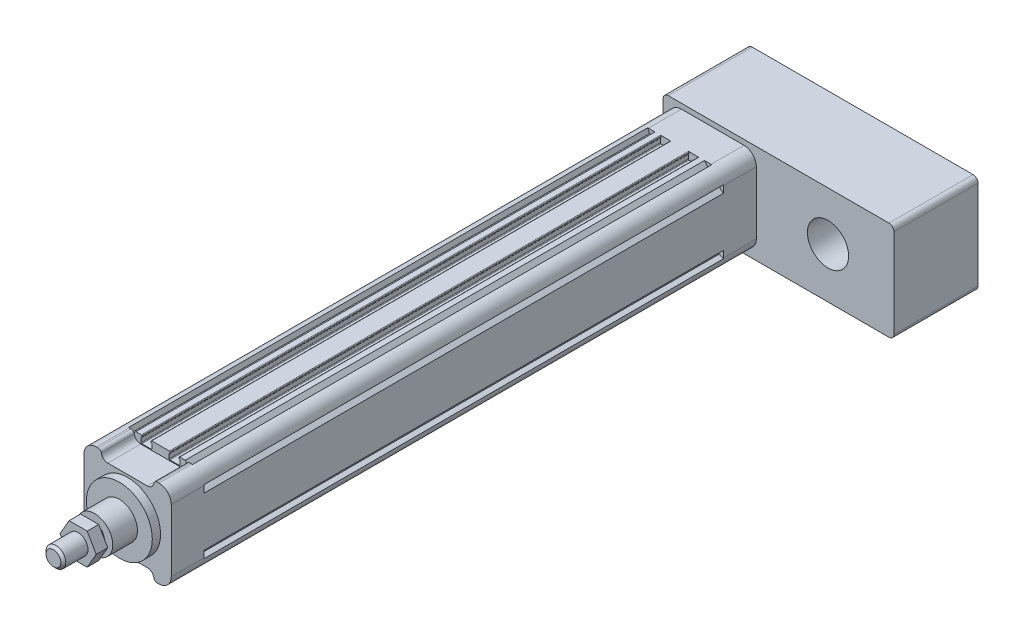
SolidWorks part; units mm, degrees
ref_plane "Front" through (0, 0, 0) normal (0, 0, 1) x (1, 0, 0)
ref_plane "Top" through (0, 0, 0) normal (0, 1, 0) x (1, 0, 0)
ref_plane "Right" through (0, 0, 0) normal (1, 0, 0) x (0, 0, -1)
sketch "草图1" plane through (0, 0, 0) normal (0, 0, 1) x (1, 0, 0)
  line L0 (19.7737, 3) -> (23.3, 3)
  line L1 (23.3, 3) -> (23.3, -3)
  line L2 (23.3, -3) -> (19.7737, -3)
  line L3 (-19.7737, -3) -> (-23.3, -3)
  line L4 (-23.3, -3) -> (-23.3, 3)
  line L5 (-23.3, 3) -> (-19.7737, 3)
  line L6 (-18.2, 24) -> (-19.4434, 26.4869)
  line L7 (-26.4869, 19.4434) -> (-24, 18.2)
  line L8 (-24, 18.2) -> (-24, 17.1)
  line L9 (-24, 17.1) -> (-26.5, 15)
  line L10 (-26.5, 15) -> (-26.5, -15)
  line L11 (-26.5, -15) -> (-24, -17.1)
  line L12 (-24, -17.1) -> (-24, -18.2)
  line L13 (-24, -18.2) -> (-26.4869, -19.4434)
  line L14 (-19.4434, -26.4869) -> (-18.2, -24)
  line L15 (-18.2, -24) -> (-17.1, -24)
  line L16 (-17.1, -24) -> (-15, -26.5)
  line L17 (-15, -26.5) -> (-11.65, -26.5)
  line L18 (-11.25, -26.1) -> (-11.25, -25.6)
  line L19 (-11.65, -25.2) -> (-11.75, -25.2)
  line L20 (-11.75, -25.2) -> (-11.75, -22.4)
  line L21 (-11.35, -22) -> (-5.65, -22)
  line L22 (-5.25, -22.4) -> (-5.25, -25.2)
  line L23 (-5.25, -25.2) -> (-5.35, -25.2)
  line L24 (-5.75, -25.6) -> (-5.75, -26.1)
  line L25 (-5.35, -26.5) -> (5.35, -26.5)
  line L26 (5.75, -26.1) -> (5.75, -25.6)
  line L27 (5.35, -25.2) -> (5.25, -25.2)
  line L28 (5.25, -25.2) -> (5.25, -22.4)
  line L29 (5.65, -22) -> (11.35, -22)
  line L30 (11.75, -22.4) -> (11.75, -25.2)
  line L31 (11.75, -25.2) -> (11.65, -25.2)
  line L32 (11.25, -25.6) -> (11.25, -26.1)
  line L33 (11.65, -26.5) -> (15, -26.5)
  line L34 (15, -26.5) -> (17.1, -24)
  line L35 (17.1, -24) -> (18.2, -24)
  line L36 (18.2, -24) -> (19.4434, -26.4869)
  line L37 (26.4869, -19.4434) -> (24, -18.2)
  line L38 (24, -18.2) -> (24, -17.1)
  line L39 (24, -17.1) -> (26.5, -15)
  line L40 (26.5, -15) -> (26.5, 15)
  line L41 (26.5, 15) -> (24, 17.1)
  line L42 (24, 17.1) -> (24, 18.2)
  line L43 (24, 18.2) -> (26.4869, 19.4434)
  line L44 (19.4434, 26.4869) -> (18.2, 24)
  line L45 (18.2, 24) -> (17.1, 24)
  line L46 (17.1, 24) -> (15, 26.5)
  line L47 (15, 26.5) -> (11.65, 26.5)
  line L48 (11.25, 26.1) -> (11.25, 25.6)
  line L49 (11.65, 25.2) -> (11.75, 25.2)
  line L50 (11.75, 25.2) -> (11.75, 22.4)
  line L51 (11.35, 22) -> (5.65, 22)
  line L52 (5.25, 22.4) -> (5.25, 25.2)
  line L53 (5.25, 25.2) -> (5.35, 25.2)
  line L54 (5.75, 25.6) -> (5.75, 26.1)
  line L55 (5.35, 26.5) -> (-5.35, 26.5)
  line L56 (-5.75, 26.1) -> (-5.75, 25.6)
  line L57 (-5.35, 25.2) -> (-5.25, 25.2)
  line L58 (-5.25, 25.2) -> (-5.25, 22.4)
  line L59 (-5.65, 22) -> (-11.35, 22)
  line L60 (-11.75, 22.4) -> (-11.75, 25.2)
  line L61 (-11.75, 25.2) -> (-11.65, 25.2)
  line L62 (-11.25, 25.6) -> (-11.25, 26.1)
  line L63 (-11.65, 26.5) -> (-15, 26.5)
  line L64 (-15, 26.5) -> (-17.1, 24)
  line L65 (-17.1, 24) -> (-18.2, 24)
  arc A0 (19.7737, 3) -> (-19.7737, 3) centre (0, 0) ccw
  arc A1 (-19.7737, -3) -> (19.7737, -3) centre (0, 0) ccw
  circle A2 centre (19, 19) radius 2.1
  circle A3 centre (19, -19) radius 2.1
  circle A4 centre (-19, -19) radius 2.1
  circle A5 centre (-19, 19) radius 2.1
  arc A6 (-19.4434, 26.4869) -> (-26.4869, 19.4434) centre (-19, 19) ccw
  arc A7 (-26.4869, -19.4434) -> (-19.4434, -26.4869) centre (-19, -19) ccw
  arc A8 (-11.65, -26.5) -> (-11.25, -26.1) centre (-11.65, -26.1) ccw
  arc A9 (-11.25, -25.6) -> (-11.65, -25.2) centre (-11.65, -25.6) ccw
  arc A10 (-11.35, -22) -> (-11.75, -22.4) centre (-11.35, -22.4) ccw
  arc A11 (-5.25, -22.4) -> (-5.65, -22) centre (-5.65, -22.4) ccw
  arc A12 (-5.35, -25.2) -> (-5.75, -25.6) centre (-5.35, -25.6) ccw
  arc A13 (-5.75, -26.1) -> (-5.35, -26.5) centre (-5.35, -26.1) ccw
  arc A14 (5.35, -26.5) -> (5.75, -26.1) centre (5.35, -26.1) ccw
  arc A15 (5.75, -25.6) -> (5.35, -25.2) centre (5.35, -25.6) ccw
  arc A16 (5.65, -22) -> (5.25, -22.4) centre (5.65, -22.4) ccw
  arc A17 (11.75, -22.4) -> (11.35, -22) centre (11.35, -22.4) ccw
  arc A18 (11.65, -25.2) -> (11.25, -25.6) centre (11.65, -25.6) ccw
  arc A19 (11.25, -26.1) -> (11.65, -26.5) centre (11.65, -26.1) ccw
  arc A20 (19.4434, -26.4869) -> (26.4869, -19.4434) centre (19, -19) ccw
  arc A21 (26.4869, 19.4434) -> (19.4434, 26.4869) centre (19, 19) ccw
  arc A22 (11.65, 26.5) -> (11.25, 26.1) centre (11.65, 26.1) ccw
  arc A23 (11.25, 25.6) -> (11.65, 25.2) centre (11.65, 25.6) ccw
  arc A24 (11.35, 22) -> (11.75, 22.4) centre (11.35, 22.4) ccw
  arc A25 (5.25, 22.4) -> (5.65, 22) centre (5.65, 22.4) ccw
  arc A26 (5.35, 25.2) -> (5.75, 25.6) centre (5.35, 25.6) ccw
  arc A27 (5.75, 26.1) -> (5.35, 26.5) centre (5.35, 26.1) ccw
  arc A28 (-5.35, 26.5) -> (-5.75, 26.1) centre (-5.35, 26.1) ccw
  arc A29 (-5.75, 25.6) -> (-5.35, 25.2) centre (-5.35, 25.6) ccw
  arc A30 (-5.65, 22) -> (-5.25, 22.4) centre (-5.65, 22.4) ccw
  arc A31 (-11.75, 22.4) -> (-11.35, 22) centre (-11.35, 22.4) ccw
  arc A32 (-11.65, 25.2) -> (-11.25, 25.6) centre (-11.65, 25.6) ccw
  arc A33 (-11.25, 26.1) -> (-11.65, 26.5) centre (-11.65, 26.1) ccw
extrude "凸台-拉伸1" add sketch "草图1" along normal blind 315
sketch "草图6" plane through (0, 0, 315) normal (0, 0, 1) x (1, 0, 0)
  line L0 (0, 0) -> (19, 0) construction
  line L2 (-26.5, -19) -> (-26.5, 19)
  line L3 (-19, 26.5) -> (-17.9161, 26.5)
  line L4 (26.5, -19) -> (26.5, 19)
  line L5 (-26.5, -26.5) -> (26.5, 26.5) construction
  line L6 (-26.5, 26.5) -> (26.5, -26.5) construction
  line L7 (-12, 21.5) -> (12, 21.5)
  line L9 (19, 26.5) -> (17.9161, 26.5)
  line L10 (19, -26.5) -> (17.9161, -26.5)
  line L11 (-12, -21.5) -> (12, -21.5)
  line L12 (-19, -26.5) -> (-17.9161, -26.5)
  arc A0 (12, 21.5) -> (15.9441, 24.8333) centre (12, 25.5) ccw
  arc A1 (-15.9441, 24.8333) -> (-12, 21.5) centre (-12, 25.5) ccw
  arc A2 (-15.9441, 24.8333) -> (-17.9161, 26.5) centre (-17.9161, 24.5) ccw
  arc A3 (15.9441, 24.8333) -> (17.9161, 26.5) centre (17.9161, 24.5) cw
  arc A4 (-26.5, -19) -> (-19, -26.5) centre (-19, -19) ccw
  arc A5 (19, -26.5) -> (26.5, -19) centre (19, -19) ccw
  arc A6 (26.5, 19) -> (19, 26.5) centre (19, 19) ccw
  arc A7 (-26.5, 19) -> (-19, 26.5) centre (-19, 19) cw
  arc A8 (15.9441, -24.8333) -> (17.9161, -26.5) centre (17.9161, -24.5) ccw
  arc A9 (12, -21.5) -> (15.9441, -24.8333) centre (12, -25.5) cw
  arc A10 (-15.9441, -24.8333) -> (-12, -21.5) centre (-12, -25.5) cw
  arc A11 (-15.9441, -24.8333) -> (-17.9161, -26.5) centre (-17.9161, -24.5) cw
  point P0 (0, 0)
  point P9 (0, 21.5)
  point P13 (20, 20.8461)
  point P16 (-12, 20.8461)
  dimension "D5" = 4
  dimension "D6" = 2
  dimension "D7" = 2
  dimension "D9" = 7.5
  dimension "D1" = 53
  dimension "D2" = 53
  dimension "D3" = 26.5
  dimension "D4" = 24
  dimension "D8" = 5
extrude "凸台-拉伸2" add sketch "草图6" along normal blind 20
sketch "草图7" plane through (0, 0, 335) normal (0, 0, 1) x (1, 0, 0)
  circle A0 centre (0, 0) radius 20
  dimension "D1" = 40
extrude "凸台-拉伸3" add sketch "草图7" along normal blind 5
sketch "草图9" plane through (0, 0, 340) normal (0, 0, 1) x (1, 0, 0)
  circle A0 centre (0, 0) radius 11
  dimension "D1" = 22
extrude "凸台-拉伸4" add sketch "草图9" along normal blind 15
sketch "草图10" plane through (0, 0, 355) normal (0, 0, 1) x (1, 0, 0)
  circle A0 centre (0, 0) radius 6
  dimension "D1" = 12
extrude "凸台-拉伸5" add sketch "草图10" along normal blind 25
sketch "草图11" plane through (0, 0, 0) normal (0, 0, -1) x (-1, 0, 0)
  line L1 (-19, -26.5) -> (19, -26.5)
  line L2 (-26.5, -19) -> (-26.5, 19)
  line L3 (-19, 26.5) -> (19, 26.5)
  line L4 (26.5, -19) -> (26.5, 19)
  line L5 (-26.5, -26.5) -> (26.5, 26.5) construction
  line L6 (-26.5, 26.5) -> (26.5, -26.5) construction
  arc A0 (-26.5, -19) -> (-19, -26.5) centre (-19, -19) ccw
  arc A1 (19, -26.5) -> (26.5, -19) centre (19, -19) ccw
  arc A2 (26.5, 19) -> (19, 26.5) centre (19, 19) ccw
  arc A3 (-26.5, 19) -> (-19, 26.5) centre (-19, 19) cw
  point P0 (0, 0)
  dimension "D3" = 7.5
  dimension "D1" = 53
  dimension "D2" = 53
extrude "凸台-拉伸6" add sketch "草图11" along normal blind 20
sketch "草图12" plane through (0, 0, -20) normal (0, 0, -1) x (-1, 0, 0)
  line L1 (-107, -30.4042) -> (27, -30.4042)
  line L2 (-110, -27.4042) -> (-110, 26.5958)
  line L3 (-107, 29.5958) -> (27, 29.5958)
  line L4 (30, -27.4042) -> (30, 26.5958)
  line L5 (-110, -30.4042) -> (30, 29.5958) construction
  line L6 (-110, 29.5958) -> (30, -30.4042) construction
  arc A0 (27, 29.5958) -> (30, 26.5958) centre (27, 26.5958) cw
  arc A1 (30, -27.4042) -> (27, -30.4042) centre (27, -27.4042) cw
  arc A2 (-110, -27.4042) -> (-107, -30.4042) centre (-107, -27.4042) ccw
  arc A3 (-110, 26.5958) -> (-107, 29.5958) centre (-107, 26.5958) cw
  point P0 (-40, -0.4042)
  dimension "D4" = 3
  dimension "D1" = 60
  dimension "D2" = 140
  dimension "D3" = 30
extrude "凸台-拉伸7" add sketch "草图12" along normal blind 51
sketch "草图13" plane through (0, 0, -20) normal (0, 0, 1) x (1, 0, 0)
  circle A0 centre (70, 0) radius 12.5
  dimension "D2" = 25
  dimension "D1" = 70
extrude "切除-拉伸2" cut sketch "草图13" against normal blind 30
hole_wizard "M6 螺纹孔1" positions "草图14" profile "草图15" tap size "M6" standard "GB"
sketch "草图14" plane through (0, 0, -71) normal (0, 0, -1) x (-1, 0, 0)
  line L0 (30, -27.4042) -> (30, 26.5958) construction
  point P0 (19, -19)
  dimension "D1" = 11
  dimension "D2" = 19
sketch "草图15" plane through (-19, -19, -71) normal (1, 0, 0) x (0, 1, 0)
  line L0 (0, 0) -> (0, 16.5022)
  line L1 (0, 16.5022) -> (2.5, 15)
  line L2 (2.5, 15) -> (2.5, 0)
  line L5 (2.5, 0) -> (0, 0)
  line L10 (0, 16.5022) -> (-2.5, 15) construction
  line L11 (0, -6.35) -> (0, 107.95) construction
  dimension "螺纹孔钻头直径" = 5
  dimension "螺纹孔钻头深度" = 15
  dimension "导头角度" = 118
cosmetic thread "孔螺蚊线4" parameters "D1"=12, "D2"=6
pattern_linear "阵列(线性)1" count 2 spacing 38 along (0, 1, 0) count 2 spacing 38 along (1, 0, 0) of "M6 螺纹孔1"
hole_wizard "M6 螺纹孔2" positions "草图16" profile "草图17" tap size "M6" standard "GB"
sketch "草图16" plane through (0, 0, -71) normal (0, 0, -1) x (-1, 0, 0)
  circle A1 centre (-19, 19) radius 2.5 construction
  circle A2 centre (-19, -19) radius 2.5 construction
  point P0 (-84, -19)
  point P2 (-84, 19)
  dimension "D3" = 65
  dimension "D1" = 19
  dimension "D2" = 19
  dimension "D4" = 65
sketch "草图17" plane through (84, -19, -71) normal (1, 0, 0) x (0, 1, 0)
  line L0 (0, 0) -> (0, 16.5022)
  line L1 (0, 16.5022) -> (2.5, 15)
  line L2 (2.5, 15) -> (2.5, 0)
  line L5 (2.5, 0) -> (0, 0)
  line L10 (0, 16.5022) -> (-2.5, 15) construction
  line L11 (0, -6.35) -> (0, 107.95) construction
  dimension "螺纹孔钻头直径" = 5
  dimension "螺纹孔钻头深度" = 15
  dimension "导头角度" = 118
cosmetic thread "孔螺蚊线5" parameters "D1"=12, "D2"=6
cosmetic thread "孔螺蚊线6" parameters "D1"=12, "D2"=6
hole_wizard "M6 螺纹孔3" positions "草图19" profile "草图20" tap size "M6" standard "GB"
sketch "草图19" plane through (-26.5, 0, 0) normal (-1, 0, 0) x (0, 0, 1)
  line L0 (335, 19) -> (335, -19) construction
  point P0 (325, 11)
  point P2 (325, -11)
  dimension "D1" = 10
  dimension "D2" = 10
  dimension "D3" = 22
  dimension "D4" = 11
sketch "草图20" plane through (-26.5, 11, 325) normal (0, 1, 0) x (0, 0, 1)
  line L0 (0, 0) -> (0, 16.5022)
  line L1 (0, 16.5022) -> (2.5, 15)
  line L2 (2.5, 15) -> (2.5, 0)
  line L5 (2.5, 0) -> (0, 0)
  line L10 (0, 16.5022) -> (-2.5, 15) construction
  line L11 (0, -6.35) -> (0, 107.95) construction
  dimension "螺纹孔钻头直径" = 5
  dimension "螺纹孔钻头深度" = 15
  dimension "导头角度" = 118
cosmetic thread "孔螺蚊线7" parameters "D1"=12, "D2"=6
cosmetic thread "孔螺蚊线8" parameters "D1"=12, "D2"=6
hole_wizard "M6 螺纹孔4" positions "草图21" profile "草图22" tap size "M6" standard "GB"
sketch "草图21" plane through (-26.5, 0, 0) normal (-1, 0, 0) x (0, 0, 1)
  line L0 (-20, -27.4042) -> (-20, 26.5958) construction
  line L1 (-20, -19) -> (-20, 19) construction
  point P0 (-10, 11)
  point P2 (-10, -11)
  dimension "D1" = 10
  dimension "D2" = 10
  dimension "D3" = 11
  dimension "D4" = 11
sketch "草图22" plane through (-26.5, 11, -10) normal (0, 1, 0) x (0, 0, 1)
  line L0 (0, 0) -> (0, 16.5022)
  line L1 (0, 16.5022) -> (2.5, 15)
  line L2 (2.5, 15) -> (2.5, 0)
  line L5 (2.5, 0) -> (0, 0)
  line L10 (0, 16.5022) -> (-2.5, 15) construction
  line L11 (0, -6.35) -> (0, 107.95) construction
  dimension "螺纹孔钻头直径" = 5
  dimension "螺纹孔钻头深度" = 15
  dimension "导头角度" = 118
cosmetic thread "孔螺蚊线9" parameters "D1"=12, "D2"=6
cosmetic thread "孔螺蚊线10" parameters "D1"=12, "D2"=6
chamfer "倒角1" distance 1.5 angle 45 1 edges at (6, 0, 380)
sketch "草图23" plane through (0, 0, 355) normal (0, 0, 1) x (1, 0, 0)
  line L1 (10.9697, 0) -> (5.4848, 9.5)
  line L2 (5.4848, 9.5) -> (-5.4848, 9.5)
  line L3 (-5.4848, 9.5) -> (-10.9697, 0)
  line L4 (-10.9697, 0) -> (-5.4848, -9.5)
  line L5 (-5.4848, -9.5) -> (5.4848, -9.5)
  line L6 (5.4848, -9.5) -> (10.9697, 0)
  circle A0 centre (0, 0) radius 9.5 construction
  dimension "D1" = 19
extrude "凸台-拉伸8" add sketch "草图23" along normal blind 7 from offset 3
